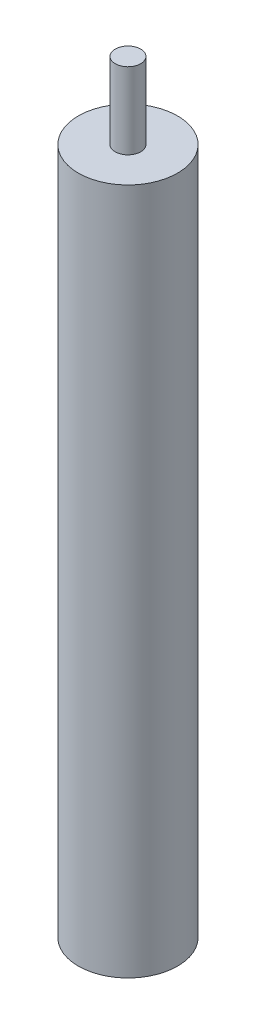
SolidWorks part; units mm, degrees
ref_plane "Front Plane" through (0, 0, 0) normal (0, 0, 1) x (1, 0, 0)
ref_plane "Top Plane" through (0, 0, 0) normal (0, 1, 0) x (1, 0, 0)
ref_plane "Right Plane" through (0, 0, 0) normal (1, 0, 0) x (0, 0, -1)
sketch "Sketch1" plane through (0, 0, 0) normal (0, 1, 0) x (1, 0, 0)
  circle A0 centre (-2.9492, 0.3338) radius 1.95
  dimension "D1" = 3.9
extrude "Boss-Extrude1" add sketch "Sketch1" along normal blind 27
sketch "Sketch2" plane through (0, 27, 0) normal (0, 1, 0) x (1, 0, 0)
  circle A0 centre (-2.9492, 0.3338) radius 0.5
  dimension "D1" = 1
extrude "Boss-Extrude2" add sketch "Sketch2" along normal blind 3
